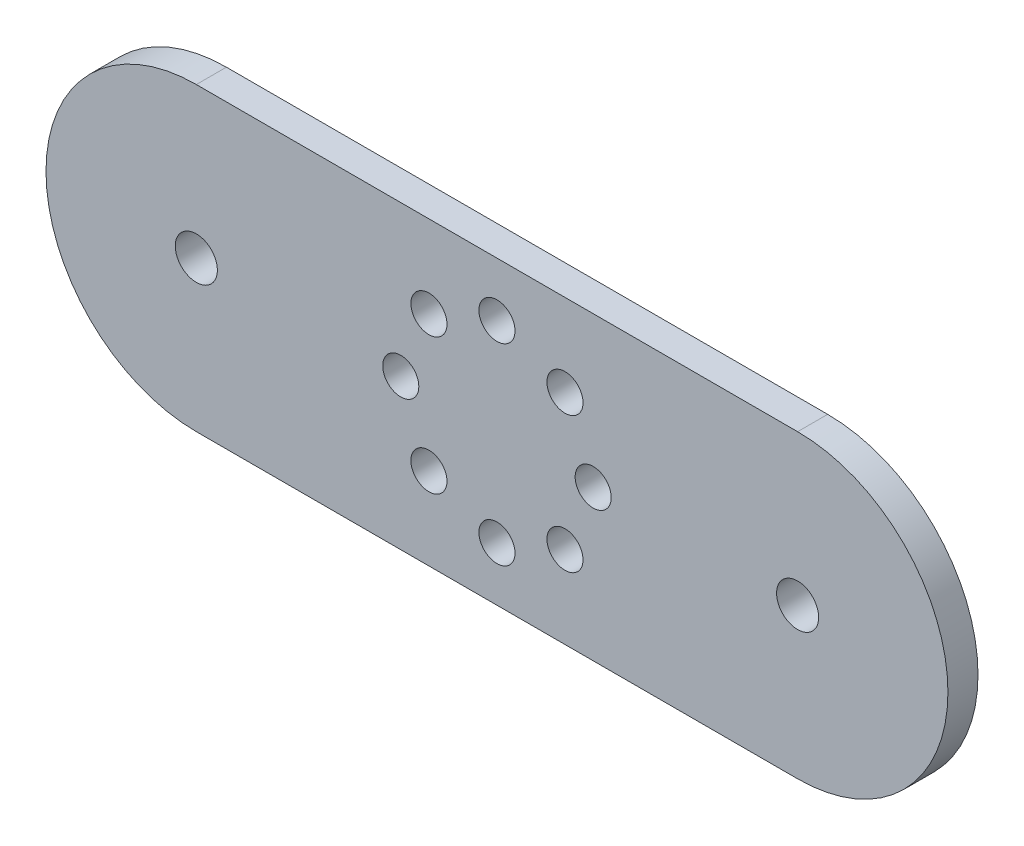
SolidWorks part; units mm, degrees
ref_plane "前视基准面" through (0, 0, 0) normal (0, 0, 1) x (1, 0, 0)
ref_plane "上视基准面" through (0, 0, 0) normal (0, 1, 0) x (1, 0, 0)
ref_plane "右视基准面" through (0, 0, 0) normal (1, 0, 0) x (0, 0, -1)
sketch "草图1" plane through (0, 0, 0) normal (0, 0, 1) x (1, 0, 0)
  line L0 (-50, 0) -> (50, 0) construction
  line L1 (-50, 25) -> (50, 25)
  line L2 (-50, -25) -> (50, -25)
  arc A0 (-50, 25) -> (-50, -25) centre (-50, 0) ccw
  arc A1 (50, -25) -> (50, 25) centre (50, 0) ccw
  circle A2 centre (16, 0) radius 3
  circle A3 centre (11.3137, -11.3137) radius 3
  circle A4 centre (0, -16) radius 3
  circle A5 centre (-11.3137, -11.3137) radius 3
  circle A6 centre (-16, 0) radius 3
  circle A7 centre (-11.3137, 11.3137) radius 3
  circle A8 centre (0, 16) radius 3
  circle A9 centre (11.3137, 11.3137) radius 3
  circle A10 centre (-50, 0) radius 3.5
  circle A11 centre (50, 0) radius 3.5
  point P3 (0, 0)
  dimension "D3" = 6
  dimension "D5" = 7
  dimension "D6" = 7
  dimension "D1" = 50
  dimension "D2" = 100
  dimension "D4" = 16
extrude "凸台-拉伸1" add sketch "草图1" along normal blind 5
